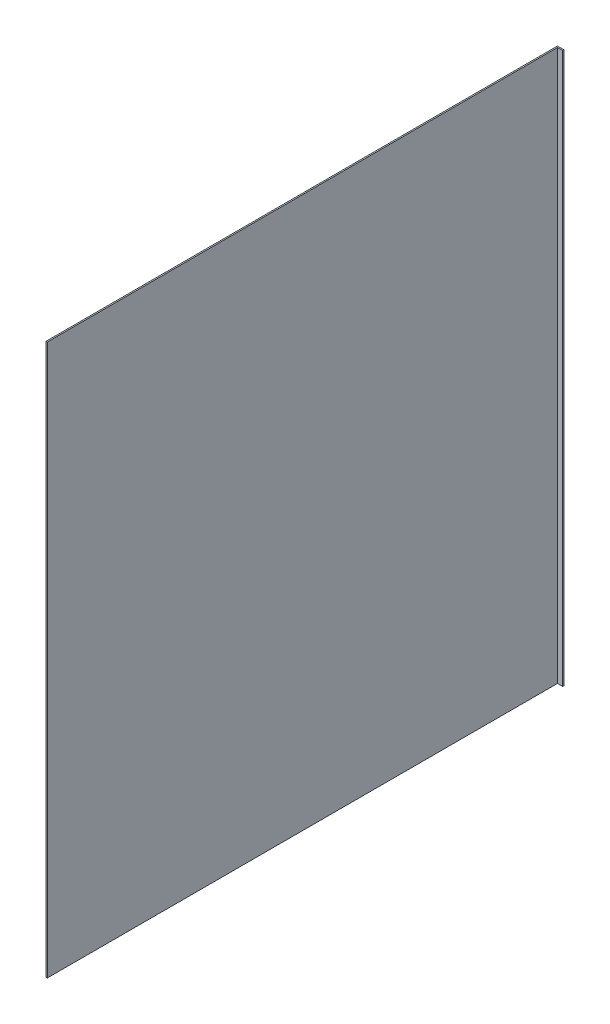
SolidWorks part; units mm, degrees
ref_plane "Front Plane" through (0, 0, 0) normal (0, 0, 1) x (1, 0, 0)
ref_plane "Top Plane" through (0, 0, 0) normal (0, 1, 0) x (1, 0, 0)
ref_plane "Right Plane" through (0, 0, 0) normal (1, 0, 0) x (0, 0, -1)
other "Configuration Table"
sketch "Sketch1" plane through (0, 0, 0) normal (0, 1, 0) x (1, 0, 0)
  line L0 (140, 800) -> (150, 800)
  line L1 (150, 800) -> (150, 798)
  line L2 (150, 798) -> (142, 798)
  line L3 (142, 798) -> (142, 20)
  line L4 (142, 20) -> (140, 20)
  line L5 (140, 20) -> (140, 800)
extrude "PACK_sarjor_L_kilavuz_1_1" add sketch "Sketch1" along normal blind 840 from offset 1040 separate body
